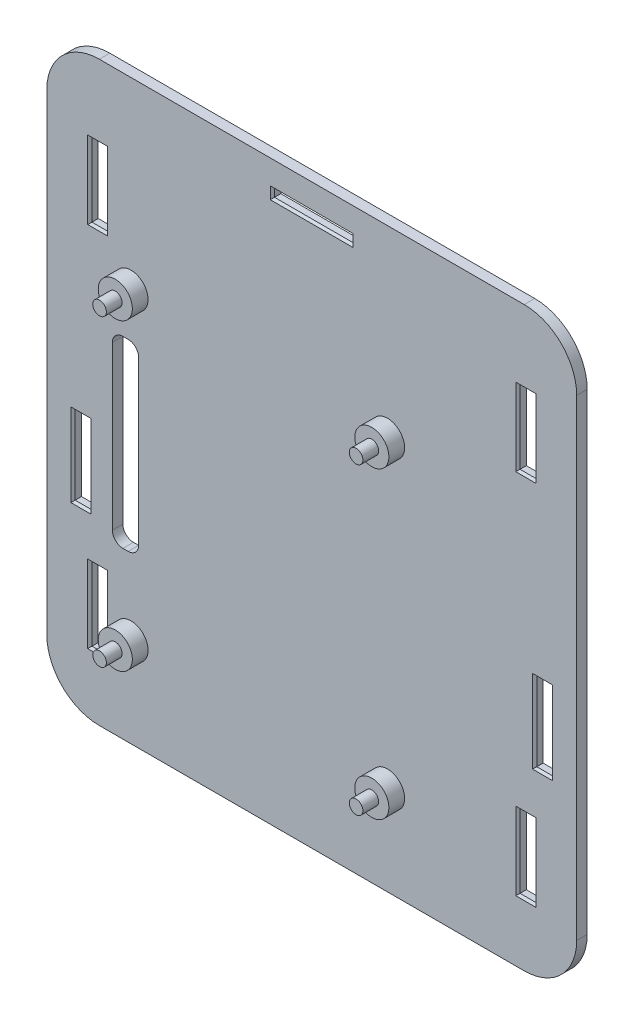
SolidWorks part; units mm, degrees
material "PE Low/Medium Density"
ref_plane "Front Plane" through (0, 0, 0) normal (0, 0, 1) x (1, 0, 0)
ref_plane "Top Plane" through (0, 0, 0) normal (0, 1, 0) x (1, 0, 0)
ref_plane "Right Plane" through (0, 0, 0) normal (1, 0, 0) x (0, 0, -1)
sketch "Sketch1" plane through (0, 0, 0) normal (0, 0, 1) x (1, 0, 0)
  line L0 (48, 82.1) -> (37, 82.1) construction
  line L1 (-8, 87.1) -> (93, 87.1)
  line L2 (-8, 87.1) -> (-8, -22.9)
  line L3 (-8, -22.9) -> (93, -22.9)
  line L4 (93, 87.1) -> (93, -22.9)
  line L5 (88, 11.6) -> (88, -12.4009) construction
  line L6 (-3, 26.6) -> (-3, 40.6) construction
  dimension "D1" = 5
  dimension "D2" = 5
  dimension "D3" = 5
  dimension "D4" = 110
extrude "Boss-Extrude1" add sketch "Sketch1" along normal blind 2
sketch "Sketch3" plane through (0, 0, 2) normal (0, 0, 1) x (1, 0, 0)
  line L1 (35, 82.1) -> (50, 82.1)
  line L2 (35, 82.1) -> (35, 80.6)
  line L3 (35, 80.6) -> (50, 80.6)
  line L4 (50, 82.1) -> (50, 80.6)
  line L5 (-3, 26.6) -> (0, 26.6)
  line L6 (-3, 26.6) -> (-3, 11.6)
  line L7 (-3, 11.6) -> (0, 11.6)
  line L8 (0, 26.6) -> (0, 11.6)
  line L9 (85, 26.6) -> (88, 26.6)
  line L10 (85, 26.6) -> (85, 11.6)
  line L11 (85, 11.6) -> (88, 11.6)
  line L12 (88, 26.6) -> (88, 11.6)
extrude "Cut-Extrude1" cut sketch "Sketch3" against normal through all
sketch "Sketch7" plane through (0, 0, 2) normal (0, 0, 1) x (1, 0, 0)
  circle A0 centre (8.05, 52.05) radius 1.3 construction
  circle A1 centre (8.05, 52.05) radius 1.3 construction
  circle A2 centre (8.05, -5.85) radius 1.3 construction
  circle A3 centre (8.05, -5.85) radius 1.3 construction
  circle A4 centre (56.95, -5.85) radius 1.3 construction
  circle A5 centre (56.95, -5.85) radius 1.3 construction
  circle A6 centre (56.95, 52.05) radius 1.3 construction
  circle A7 centre (56.95, 52.05) radius 1.3 construction
  circle A8 centre (8.05, 52.05) radius 3.25
  circle A9 centre (56.95, 52.05) radius 3.25
  circle A10 centre (8.05, -5.85) radius 3.25
  circle A11 centre (56.95, -5.85) radius 3.25
  dimension "D1" = 6.5
extrude "Boss-Extrude2" add sketch "Sketch7" along normal up to surface (3 mm away)
sketch "Sketch8" plane through (0, 0, 5) normal (0, 0, 1) x (1, 0, 0)
  circle A0 centre (8.05, -5.85) radius 1.3 construction
  circle A1 centre (56.95, -5.85) radius 1.3 construction
  circle A2 centre (56.95, 52.05) radius 1.3 construction
  circle A3 centre (8.05, 52.05) radius 1.3 construction
  circle A4 centre (8.05, -5.85) radius 1.3
  circle A5 centre (56.95, -5.85) radius 1.3
  circle A6 centre (56.95, 52.05) radius 1.3
  circle A7 centre (8.05, 52.05) radius 1.3
extrude "Boss-Extrude3" add sketch "Sketch8" along normal blind 3
chamfer "Chamfer2" distance 0.4 angle 45 24 edges at (42.5, 82.1, 0) (50, 81.35, 0) (35, 81.35, 0) (42.5, 80.6, 0) (50, 81.35, 2) (42.5, 80.6, 2) (35, 81.35, 2) (42.5, 82.1, 2) (85, 19.1, 2) (86.5, 11.6, 2) (88, 19.1, 2) (86.5, 26.6, 2) (86.5, 26.6, 0) (88, 19.1, 0) (86.5, 11.6, 0) (85, 19.1, 0) (-1.5, 11.6, 0) (0, 19.1, 0) (-1.5, 26.6, 0) (-3, 19.1, 0) (-1.5, 11.6, 2) (0, 19.1, 2) (-1.5, 26.6, 2) (-3, 19.1, 2)
sketch "Sketch9" plane through (0, 0, 0) normal (0, 0, -1) x (-1, 0, 0)
  line L0 (-84.8, 59.1) -> (-84.8, 61.1) construction
  line L1 (-84.8, 71.1) -> (-84.8, 61.1) construction
  line L3 (-3.2, 59.1) -> (-3.2, 61.1) construction
  line L4 (-84.8, 1.1) -> (-84.8, -8.9)
  line L5 (-81.8, 1.1) -> (-84.8, 1.1)
  line L6 (-81.8, -8.9) -> (-81.8, 1.1)
  line L7 (-81.8, 3.1) -> (-84.8, 3.1)
  line L8 (-84.8, 3.1) -> (-84.8, -10.9)
  line L9 (-84.8, -8.9) -> (-81.8, -8.9)
  line L10 (-81.8, -10.9) -> (-81.8, 3.1)
  line L11 (-84.8, -10.9) -> (-81.8, -10.9)
  line L12 (-84.8, 71.1) -> (-84.8, 61.1)
  line L13 (-81.8, 71.1) -> (-84.8, 71.1)
  line L14 (-81.8, 61.1) -> (-81.8, 71.1)
  line L15 (-81.8, 73.1) -> (-84.8, 73.1)
  line L16 (-84.8, 73.1) -> (-84.8, 59.1)
  line L17 (-84.8, 61.1) -> (-81.8, 61.1)
  line L18 (-81.8, 59.1) -> (-81.8, 73.1)
  line L19 (-84.8, 59.1) -> (-81.8, 59.1)
  line L20 (-3.2, 1.1) -> (-3.2, -8.9)
  line L21 (-0.2, 1.1) -> (-3.2, 1.1)
  line L22 (-0.2, -8.9) -> (-0.2, 1.1)
  line L23 (-0.2, 3.1) -> (-3.2, 3.1)
  line L24 (-3.2, 3.1) -> (-3.2, -10.9)
  line L25 (-3.2, -8.9) -> (-0.2, -8.9)
  line L26 (-0.2, -10.9) -> (-0.2, 3.1)
  line L27 (-3.2, -10.9) -> (-0.2, -10.9)
  line L28 (-3.2, 71.1) -> (-3.2, 61.1)
  line L29 (-0.2, 71.1) -> (-3.2, 71.1)
  line L30 (-0.2, 61.1) -> (-0.2, 71.1)
  line L31 (-0.2, 73.1) -> (-3.2, 73.1)
  line L32 (-3.2, 73.1) -> (-3.2, 59.1)
  line L33 (-3.2, 61.1) -> (-0.2, 61.1)
  line L34 (-0.2, 59.1) -> (-0.2, 73.1)
  line L35 (-3.2, 59.1) -> (-0.2, 59.1)
  line L36 (-3.2, 3.1) -> (-0.2, 3.1) construction
  dimension "D1" = 0
  dimension "D2" = 0
  dimension "D3" = 0
  dimension "D4" = 0
extrude "Cut-Extrude2" cut sketch "Sketch9" against normal blind 5
chamfer "Chamfer3" distance 0.4 angle 45 32 edges at (1.7, 59.1, 0) (3.2, 66.1, 0) (0.2, 66.1, 0) (1.7, 73.1, 0) (1.7, -10.9, 0) (0.2, -3.9, 0) (1.7, 3.1, 0) (3.2, -3.9, 0) (81.8, 66.1, 0) (83.3, 59.1, 0) (83.3, 73.1, 0) (84.8, 66.1, 0) (1.7, -10.9, 2) (0.2, -3.9, 2) (3.2, -3.9, 2) (1.7, 3.1, 2) (1.7, 73.1, 2) (3.2, 66.1, 2) (1.7, 59.1, 2) (0.2, 66.1, 2) (84.8, 66.1, 2) (83.3, 73.1, 2) (83.3, 59.1, 2) (81.8, 66.1, 2) (84.8, -3.9, 2) (83.3, -10.9, 2) (83.3, 3.1, 2) (81.8, -3.9, 2) (81.8, -3.9, 0) (83.3, 3.1, 0) (83.3, -10.9, 0) (84.8, -3.9, 0)
sketch "Sketch10" plane through (0, 0, 2) normal (0, 0, 1) x (1, 0, 0)
  line L0 (4.5, 73.1) -> (4.5, -6.9) construction
  line L1 (4.5, 43.6) -> (9.5, 43.6)
  line L2 (4.5, 43.6) -> (4.5, 8.6)
  line L3 (4.5, 8.6) -> (9.5, 8.6)
  line L4 (9.5, 43.6) -> (9.5, 8.6)
  line L5 (7, -9.4) -> (58, -9.4) construction
  dimension "D1" = 5
  dimension "D2" = 35
  dimension "D3" = 18
extrude "Cut-Extrude3" cut sketch "Sketch10" against normal through all
fillet "Fillet1" radius 2 4 edges at (4.5, 43.6, 1) (9.5, 43.6, 1) (9.5, 8.6, 1) (4.5, 8.6, 1)
fillet "Fillet2" radius 10 4 edges at (93, 87.1, 1) (-8, 87.1, 1) (-8, -22.9, 1) (93, -22.9, 1)
